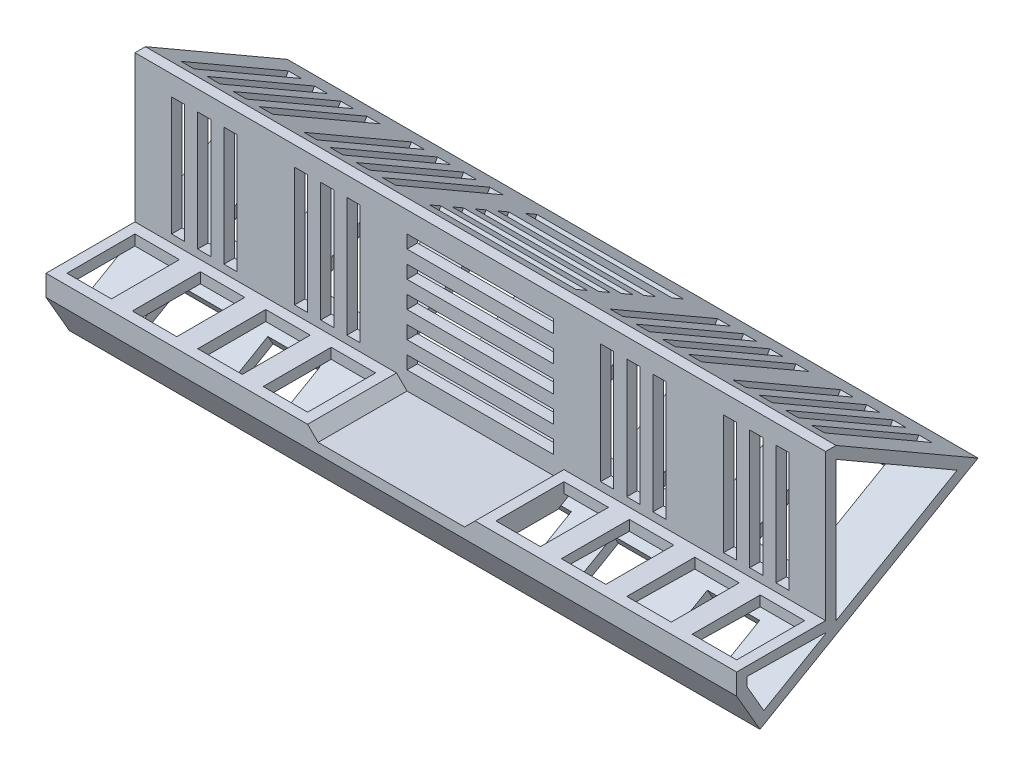
SolidWorks part; units mm, degrees
ref_plane "前视基准面" through (0, 0, 0) normal (0, 0, 1) x (1, 0, 0)
ref_plane "上视基准面" through (0, 0, 0) normal (0, 1, 0) x (1, 0, 0)
ref_plane "右视基准面" through (0, 0, 0) normal (1, 0, 0) x (0, 0, -1)
sketch "草图4" plane through (0, 0, 0) normal (0, 0, 1) x (1, 0, 0)
  line L0 (-105.5, -67.1) -> (-155.5, -67.1)
  line L2 (-105.5, -67.1) -> (-103.5, -69.1)
  line L3 (-103.5, -69.1) -> (-75.5, -69.1)
  line L4 (-75.5, -69.1) -> (-73.5, -67.1)
  line L5 (-73.5, -67.1) -> (-23.5, -67.1)
  line L7 (-155.5, -67.1) -> (-155.5, -69.1)
  line L8 (-153.5, -71.1) -> (-25.5, -71.1)
  line L9 (-23.5, -69.1) -> (-23.5, -67.1)
  line L22 (-155.5, -69.1) -> (-155.5, -71.1)
  line L23 (-155.5, -71.1) -> (-153.5, -71.1)
  line L26 (-23.5, -69.1) -> (-23.5, -71.1)
  line L27 (-23.5, -71.1) -> (-25.5, -71.1)
  dimension "D1" = 2
extrude "凸台-拉伸2" add sketch "草图4" along normal blind 17
sketch "草图5" plane through (-155.5, 0, 0) normal (-1, 0, 0) x (0, 0, 1)
  line L9 (0, -69.1) -> (-21.3616, -47.7384)
  line L13 (-21.3616, -47.7384) -> (-22.7759, -49.1526)
  line L14 (0, -69.1) -> (0, -71.1)
  line L15 (-22.7759, -49.1526) -> (-0.8284, -71.1)
  line L16 (0, -71.1) -> (-0.8284, -71.1)
sketch "草图7" plane through (-155.5, 0, 0) normal (-1, 0, 0) x (0, 0, 1)
  line L3 (0, -39.1) -> (-2, -39.1)
  line L17 (0, -39.1) -> (0, -71.1)
  line L18 (0, -71.1) -> (-0.8284, -71.1)
  line L19 (-0.8284, -71.1) -> (-29.127, -54.7618)
  line L20 (-2, -39.1) -> (-29.127, -54.7618)
  line L22 (-25.127, -54.7618) -> (-2, -68.1142)
  line L23 (-2, -41.4094) -> (-25.127, -54.7618)
  line L24 (-2, -41.4094) -> (-2, -68.1142)
  dimension "D3" = 2
extrude "凸台-拉伸6" add sketch "草图7" against normal blind 132
sketch "草图9" plane through (0, -30.2212, 13.3785) normal (0, 0.866, -0.5) x (1, 0, 0)
  line L0 (-141, 44.117) -> (-141, 20.4123)
  line L1 (-141, 20.4123) -> (-138.5, 20.4123)
  line L2 (-130.5, 31.9545) -> (-130.5, 49011.8146) construction
  line L3 (-105.5, 15.3031) -> (-155.5, 15.3031) construction
  line L4 (-48.5, -988.1854) -> (-48.5, 49011.8146) construction
  line L5 (-23.5, 15.3031) -> (-73.5, 15.3031) construction
  line L6 (-103.5, 25.4123) -> (-103.5, 27.9123)
  line L7 (-138.5, 44.117) -> (-138.5, 20.4123)
  line L12 (-141, 44.117) -> (-138.5, 44.117)
  line L74 (-146, 44.117) -> (-146, 20.4123)
  line L114 (-103.5, 25.4123) -> (-75.5, 25.4123)
  line L123 (-89.5, -963.3071) -> (-89.5, 49036.6929) construction
  line L136 (-136, 44.117) -> (-136, 20.4123)
  line L137 (-136, 44.117) -> (-133.5, 44.117)
  line L138 (-133.5, 44.117) -> (-133.5, 20.4123)
  line L139 (-136, 20.4123) -> (-133.5, 20.4123)
  line L192 (-146, 20.4123) -> (-143.5, 20.4123)
  line L193 (-143.5, 44.117) -> (-143.5, 20.4123)
  line L194 (-146, 44.117) -> (-143.5, 44.117)
  line L195 (-151, 44.117) -> (-151, 20.4123)
  line L196 (-151, 20.4123) -> (-148.5, 20.4123)
  line L197 (-148.5, 44.117) -> (-148.5, 20.4123)
  line L198 (-151, 44.117) -> (-148.5, 44.117)
  line L199 (-125, 44.117) -> (-127.5, 44.117)
  line L200 (-127.5, 44.117) -> (-127.5, 20.4123)
  line L201 (-125, 20.4123) -> (-127.5, 20.4123)
  line L202 (-125, 44.117) -> (-125, 20.4123)
  line L203 (-120, 44.117) -> (-122.5, 44.117)
  line L204 (-122.5, 44.117) -> (-122.5, 20.4123)
  line L205 (-120, 20.4123) -> (-122.5, 20.4123)
  line L206 (-120, 44.117) -> (-120, 20.4123)
  line L207 (-115, 44.117) -> (-117.5, 44.117)
  line L208 (-117.5, 44.117) -> (-117.5, 20.4123)
  line L209 (-115, 20.4123) -> (-117.5, 20.4123)
  line L210 (-115, 44.117) -> (-115, 20.4123)
  line L211 (-110, 44.117) -> (-112.5, 44.117)
  line L212 (-112.5, 44.117) -> (-112.5, 20.4123)
  line L213 (-110, 20.4123) -> (-112.5, 20.4123)
  line L214 (-110, 44.117) -> (-110, 20.4123)
  line L215 (-69, 44.117) -> (-69, 20.4123)
  line L216 (-69, 20.4123) -> (-66.5, 20.4123)
  line L217 (-66.5, 44.117) -> (-66.5, 20.4123)
  line L218 (-69, 44.117) -> (-66.5, 44.117)
  line L219 (-64, 44.117) -> (-64, 20.4123)
  line L220 (-64, 20.4123) -> (-61.5, 20.4123)
  line L221 (-61.5, 44.117) -> (-61.5, 20.4123)
  line L222 (-64, 44.117) -> (-61.5, 44.117)
  line L223 (-59, 44.117) -> (-59, 20.4123)
  line L224 (-59, 20.4123) -> (-56.5, 20.4123)
  line L225 (-56.5, 44.117) -> (-56.5, 20.4123)
  line L226 (-59, 44.117) -> (-56.5, 44.117)
  line L227 (-54, 44.117) -> (-54, 20.4123)
  line L228 (-54, 20.4123) -> (-51.5, 20.4123)
  line L229 (-51.5, 44.117) -> (-51.5, 20.4123)
  line L230 (-54, 44.117) -> (-51.5, 44.117)
  line L231 (-43, 44.117) -> (-45.5, 44.117)
  line L232 (-45.5, 44.117) -> (-45.5, 20.4123)
  line L233 (-43, 20.4123) -> (-45.5, 20.4123)
  line L234 (-43, 44.117) -> (-43, 20.4123)
  line L235 (-38, 44.117) -> (-40.5, 44.117)
  line L236 (-40.5, 44.117) -> (-40.5, 20.4123)
  line L237 (-38, 20.4123) -> (-40.5, 20.4123)
  line L238 (-38, 44.117) -> (-38, 20.4123)
  line L239 (-33, 44.117) -> (-35.5, 44.117)
  line L240 (-35.5, 44.117) -> (-35.5, 20.4123)
  line L241 (-33, 20.4123) -> (-35.5, 20.4123)
  line L242 (-33, 44.117) -> (-33, 20.4123)
  line L243 (-28, 44.117) -> (-30.5, 44.117)
  line L244 (-30.5, 44.117) -> (-30.5, 20.4123)
  line L245 (-28, 20.4123) -> (-30.5, 20.4123)
  line L246 (-28, 44.117) -> (-28, 20.4123)
  line L247 (-75.5, 25.4123) -> (-75.5, 27.9123)
  line L248 (-23.5, 18.9123) -> (-155.5, 18.9123) construction
  line L249 (-23.5, 45.617) -> (-155.5, 45.617) construction
  line L250 (-103.5, 16.3031) -> (-103.5, 31.0255) construction
  line L251 (-103.5, 20.4123) -> (-75.5, 20.4123)
  line L252 (-103.5, 20.4123) -> (-103.5, 22.9123)
  line L253 (-103.5, 22.9123) -> (-75.5, 22.9123)
  line L254 (-75.5, 20.4123) -> (-75.5, 22.9123)
  line L255 (-75.5, 16.3031) -> (-75.5, 31.0255) construction
  line L256 (-103.5, 27.9123) -> (-75.5, 27.9123)
  line L257 (-103.5, 44.117) -> (-75.5, 44.117)
  line L258 (-103.5, 44.117) -> (-103.5, 41.617)
  line L259 (-103.5, 41.617) -> (-75.5, 41.617)
  line L260 (-75.5, 44.117) -> (-75.5, 41.617)
  line L261 (-103.5, 30.4123) -> (-103.5, 32.9123)
  line L262 (-103.5, 30.4123) -> (-75.5, 30.4123)
  line L263 (-75.5, 30.4123) -> (-75.5, 32.9123)
  line L264 (-103.5, 32.9123) -> (-75.5, 32.9123)
  line L265 (-103.5, 35.4123) -> (-103.5, 37.9123)
  line L266 (-103.5, 35.4123) -> (-75.5, 35.4123)
  line L267 (-75.5, 35.4123) -> (-75.5, 37.9123)
  line L268 (-103.5, 37.9123) -> (-75.5, 37.9123)
  point P10 (-130.5, 15.3031)
  point P15 (-48.5, 15.3031)
  dimension "D1" = 2.5
  dimension "D2" = 4
  dimension "D3" = 4
  dimension "D4" = 1.5
  dimension "D5" = 1.5
extrude "切除-拉伸2" cut sketch "草图9" against normal blind 2
sketch "草图10" plane through (0, 0, 0) normal (0, 0, 1) x (1, 0, 0)
  line L7 (-143.5, -42.9094) -> (-143.5, -65.6)
  line L8 (-143.5, -42.9094) -> (-141, -42.9094)
  line L9 (-141, -42.9094) -> (-141, -65.6)
  line L10 (-143.5, -65.6) -> (-141, -65.6)
  line L11 (-138.5, -42.9094) -> (-138.5, -65.6)
  line L12 (-138.5, -42.9094) -> (-136, -42.9094)
  line L13 (-136, -42.9094) -> (-136, -65.6)
  line L14 (-138.5, -65.6) -> (-136, -65.6)
  line L18 (-122.5, -42.79) -> (-125, -42.79)
  line L19 (-125, -42.79) -> (-125, -65.6)
  line L20 (-122.5, -65.6) -> (-125, -65.6)
  line L21 (-122.5, -42.79) -> (-122.5, -65.6)
  line L22 (-117.5, -42.79) -> (-120, -42.79)
  line L23 (-120, -42.79) -> (-120, -65.6)
  line L24 (-117.5, -65.6) -> (-120, -65.6)
  line L25 (-117.5, -42.79) -> (-117.5, -65.6)
  line L26 (-112.5, -65.6) -> (-115, -65.6)
  line L27 (-115, -42.79) -> (-115, -65.6)
  line L28 (-112.5, -42.79) -> (-115, -42.79)
  line L29 (-112.5, -42.79) -> (-112.5, -65.6)
  line L30 (-66.5, -42.79) -> (-66.5, -65.6)
  line L31 (-66.5, -42.79) -> (-64, -42.79)
  line L32 (-64, -42.79) -> (-64, -65.6)
  line L33 (-66.5, -65.6) -> (-64, -65.6)
  line L34 (-61.5, -42.79) -> (-61.5, -65.6)
  line L35 (-61.5, -65.6) -> (-59, -65.6)
  line L36 (-59, -42.79) -> (-59, -65.6)
  line L37 (-61.5, -42.79) -> (-59, -42.79)
  line L38 (-56.5, -42.79) -> (-56.5, -65.6)
  line L39 (-56.5, -65.6) -> (-54, -65.6)
  line L40 (-54, -42.79) -> (-54, -65.6)
  line L41 (-56.5, -42.79) -> (-54, -42.79)
  line L42 (-40.5, -42.79) -> (-43, -42.79)
  line L43 (-43, -42.79) -> (-43, -65.6)
  line L44 (-40.5, -65.6) -> (-43, -65.6)
  line L45 (-40.5, -42.79) -> (-40.5, -65.6)
  line L46 (-35.5, -42.79) -> (-38, -42.79)
  line L47 (-38, -42.79) -> (-38, -65.6)
  line L48 (-35.5, -65.6) -> (-38, -65.6)
  line L49 (-35.5, -42.79) -> (-35.5, -65.6)
  line L50 (-30.5, -65.6) -> (-33, -65.6)
  line L51 (-33, -42.79) -> (-33, -65.6)
  line L52 (-30.5, -42.79) -> (-33, -42.79)
  line L53 (-30.5, -42.79) -> (-30.5, -65.6)
  line L54 (-148.5, -42.1594) -> (-148.5, -54.0118) construction
  line L57 (-103.5, -58.1) -> (-103.5, -60.6)
  line L58 (-103.5, -63.1) -> (-75.5, -63.1)
  line L59 (-103.5, -63.1) -> (-103.5, -65.6)
  line L60 (-103.5, -65.6) -> (-75.5, -65.6)
  line L61 (-75.5, -63.1) -> (-75.5, -65.6)
  line L62 (-103.5, -58.1) -> (-75.5, -58.1)
  line L63 (-75.5, -58.1) -> (-75.5, -60.6)
  line L64 (-103.5, -60.6) -> (-75.5, -60.6)
  line L65 (-103.5, -53.1) -> (-103.5, -55.6)
  line L66 (-103.5, -53.1) -> (-75.5, -53.1)
  line L67 (-75.5, -53.1) -> (-75.5, -55.6)
  line L68 (-103.5, -55.6) -> (-75.5, -55.6)
  line L69 (-103.5, -48.1) -> (-103.5, -50.6)
  line L70 (-103.5, -48.1) -> (-75.5, -48.1)
  line L71 (-75.5, -48.1) -> (-75.5, -50.6)
  line L72 (-103.5, -50.6) -> (-75.5, -50.6)
  line L73 (-103.5, -43.1) -> (-103.5, -45.6)
  line L74 (-103.5, -43.1) -> (-75.5, -43.1)
  line L75 (-75.5, -43.1) -> (-75.5, -45.6)
  line L76 (-103.5, -45.6) -> (-75.5, -45.6)
  line L77 (-148.5, -42.9094) -> (-146, -42.9094)
  line L78 (-148.5, -42.9094) -> (-148.5, -65.6)
  line L79 (-148.5, -65.6) -> (-146, -65.6)
  line L80 (-146, -42.9094) -> (-146, -65.6)
  dimension "D4" = 0
  dimension "D5" = 5
extrude "切除-拉伸3" cut sketch "草图10" against normal blind 2
sketch "草图11" plane through (0, -67.1, 0) normal (0, 1, 0) x (1, 0, 0)
  line L1 (-105.5, -17) -> (-105.5, 0) construction
  line L4 (-153.5, -2) -> (-145, -2)
  line L8 (-89.5, -1017) -> (-89.5, 48983) construction
  line L9 (-75.5, -17) -> (-103.5, -17) construction
  line L10 (-107.5, -2) -> (-107.5, -15)
  line L11 (-141, -2) -> (-132.5, -2)
  line L12 (-141, -15) -> (-132.5, -15)
  line L17 (-128.5, -2) -> (-120, -2)
  line L19 (-132.5, -2) -> (-132.5, -15)
  line L21 (-128.5, -2) -> (-128.5, -15)
  line L22 (-116, -15) -> (-107.5, -15)
  line L24 (-128.5, -15) -> (-120, -15)
  line L25 (-145, -2) -> (-145, -15)
  line L27 (-141, -2) -> (-141, -15)
  line L28 (-116, -2) -> (-107.5, -2)
  line L30 (-120, -2) -> (-120, -15)
  line L32 (-116, -2) -> (-116, -15)
  line L33 (-63, -2) -> (-71.5, -2)
  line L34 (-63, -2) -> (-63, -15)
  line L35 (-63, -15) -> (-71.5, -15)
  line L36 (-71.5, -2) -> (-71.5, -15)
  line L37 (-50.5, -2) -> (-59, -2)
  line L38 (-59, -2) -> (-59, -15)
  line L39 (-50.5, -15) -> (-59, -15)
  line L40 (-50.5, -2) -> (-50.5, -15)
  line L41 (-38, -2) -> (-46.5, -2)
  line L42 (-38, -2) -> (-38, -15)
  line L43 (-38, -15) -> (-46.5, -15)
  line L44 (-46.5, -2) -> (-46.5, -15)
  line L45 (-25.5, -15) -> (-25.5, -2)
  line L46 (-25.5, -2) -> (-34, -2)
  line L47 (-34, -2) -> (-34, -15)
  line L48 (-25.5, -15) -> (-34, -15)
  line L49 (-153.5, -2) -> (-153.5, -15)
  line L50 (-153.5, -15) -> (-145, -15)
  point P17 (-89.5, -17)
  dimension "D3" = 2
ref_plane "基准面5" through (-153.5, 0, 0) normal (-1, 0, 0) x (0, 0, 1)
sketch "草图12" plane through (-155.5, 0, 0) normal (-1, 0, 0) x (0, 0, 1)
  line L17 (3.1716, -71.1) -> (-0.8284, -71.1)
  line L19 (-0.8284, -71.1) -> (12.5429, -78.8199)
  line L21 (11.8108, -76.0879) -> (3.1716, -71.1)
  line L23 (17, -71.1) -> (12.5429, -78.8199)
  line L26 (14.6906, -71.1) -> (11.8108, -76.0879)
  line L27 (17, -71.1) -> (14.6906, -71.1)
extrude "凸台-拉伸7" add sketch "草图12" against normal blind 132
extrude "切除-拉伸6" cut sketch "草图11" against normal blind 2
sketch "草图13" plane through (-155.5, 0, 0) normal (-1, 0, 0) x (0, 0, 1)
  line L1 (0, -69.1) -> (15, -69.1)
  line L3 (14.6906, -71.1) -> (3.1716, -71.1)
  line L5 (3.1716, -71.1) -> (0, -69.2689)
  line L7 (14.6906, -71.1) -> (15, -70.5641)
  line L8 (15, -69.1) -> (15, -70.5641)
  line L9 (17, -67.1) -> (17, -71.1) construction
  line L10 (0, -69.1) -> (0, -69.2689)
  dimension "D1" = 2
  dimension "D2" = 2
extrude "切除-拉伸7" cut sketch "草图13" against normal blind 48
sketch "草图15" plane through (-23.5, 0, 0) normal (1, 0, 0) x (0, 0, -1)
  line L0 (-15, -68.8321) -> (-15, -70.5641)
  line L1 (-15, -70.5641) -> (-15, -67.1) construction
  line L2 (-15, -70.5641) -> (-14.6906, -71.1)
  line L3 (-14.6906, -71.1) -> (-3.1716, -71.1)
  line L4 (-3.1716, -71.1) -> (0, -69.2689)
  line L5 (0, -69.2689) -> (0, -69.1)
  line L6 (0, -69.1) -> (-15, -68.8321)
extrude "切除-拉伸8" cut sketch "草图15" against normal blind 48
sketch "草图16" plane through (0, -53.6837, -30.9943) normal (0, -0.866, -0.5) x (1, 0, 0)
  line L0 (-23.5, 32.325) -> (-155.5, 32.325) construction
  line L1 (-145.5, 28.325) -> (-135.5, 28.325)
  line L2 (-145.5, 28.325) -> (-145.5, 9.6203)
  line L3 (-145.5, 9.6203) -> (-135.5, 9.6203)
  line L4 (-135.5, 28.325) -> (-135.5, 9.6203)
  line L5 (-145.5, 45.2724) -> (-135.5, 45.2724)
  line L6 (-145.5, 45.2724) -> (-145.5, 37.6344)
  line L7 (-145.5, 37.6344) -> (-135.5, 37.6344)
  line L8 (-135.5, 45.2724) -> (-135.5, 37.6344)
  line L9 (-23.5, 5.6203) -> (-155.5, 5.6203) construction
  line L10 (-155.5, 2.1562) -> (-155.5, 50.2724) construction
  line L11 (-89.5, -961.7033) -> (-89.5, 49038.2967) construction
  line L12 (-71.5, 38.2967) -> (-107.5, 38.2967) construction
  line L13 (-109.5, 28.325) -> (-99.5, 28.325)
  line L14 (-109.5, 28.325) -> (-109.5, 9.6203)
  line L15 (-99.5, 28.325) -> (-99.5, 9.6203)
  line L16 (-109.5, 9.6203) -> (-99.5, 9.6203)
  line L17 (-135.5, 28.325) -> (-109.5, 28.325) construction
  line L18 (-127.5, 9.6203) -> (-117.5, 9.6203)
  line L19 (-127.5, 28.325) -> (-117.5, 28.325)
  line L20 (-127.5, 28.325) -> (-127.5, 9.6203)
  line L21 (-117.5, 28.325) -> (-117.5, 9.6203)
  line L22 (-69.5, 28.325) -> (-69.5, 9.6203)
  line L23 (-69.5, 9.6203) -> (-79.5, 9.6203)
  line L24 (-79.5, 28.325) -> (-79.5, 9.6203)
  line L25 (-69.5, 28.325) -> (-79.5, 28.325)
  line L26 (-51.5, 28.325) -> (-51.5, 9.6203)
  line L27 (-51.5, 28.325) -> (-61.5, 28.325)
  line L28 (-61.5, 28.325) -> (-61.5, 9.6203)
  line L29 (-51.5, 9.6203) -> (-61.5, 9.6203)
  line L30 (-33.5, 9.6203) -> (-43.5, 9.6203)
  line L31 (-43.5, 28.325) -> (-43.5, 9.6203)
  line L32 (-33.5, 28.325) -> (-43.5, 28.325)
  line L33 (-33.5, 28.325) -> (-33.5, 9.6203)
  line L34 (-107.5, 34.6344) -> (-155.5, 34.6344) construction
  line L35 (-23.5, 48.2724) -> (-155.5, 48.2724) construction
  line L36 (-109.5, 45.2724) -> (-99.5, 45.2724)
  line L37 (-99.5, 45.2724) -> (-99.5, 37.6344)
  line L38 (-109.5, 45.2724) -> (-109.5, 37.6344)
  line L39 (-109.5, 37.6344) -> (-99.5, 37.6344)
  line L40 (-127.5, 45.2724) -> (-127.5, 37.6344)
  line L41 (-127.5, 37.6344) -> (-117.5, 37.6344)
  line L42 (-117.5, 45.2724) -> (-117.5, 37.6344)
  line L43 (-127.5, 45.2724) -> (-117.5, 45.2724)
  line L44 (-69.5, 45.2724) -> (-69.5, 37.6344)
  line L45 (-69.5, 37.6344) -> (-79.5, 37.6344)
  line L46 (-79.5, 45.2724) -> (-79.5, 37.6344)
  line L47 (-69.5, 45.2724) -> (-79.5, 45.2724)
  line L48 (-51.5, 45.2724) -> (-61.5, 45.2724)
  line L49 (-61.5, 45.2724) -> (-61.5, 37.6344)
  line L50 (-51.5, 37.6344) -> (-61.5, 37.6344)
  line L51 (-51.5, 45.2724) -> (-51.5, 37.6344)
  line L52 (-33.5, 37.6344) -> (-43.5, 37.6344)
  line L53 (-43.5, 45.2724) -> (-43.5, 37.6344)
  line L54 (-33.5, 45.2724) -> (-43.5, 45.2724)
  line L55 (-33.5, 45.2724) -> (-33.5, 37.6344)
  point P19 (-89.5, 38.2967)
  dimension "D1" = 4
  dimension "D2" = 4
  dimension "D3" = 10
  dimension "D4" = 10
  dimension "D5" = 10
  dimension "D6" = 3
  dimension "D7" = 3
  dimension "D8" = 10
extrude "切除-拉伸9" cut sketch "草图16" against normal blind 2
